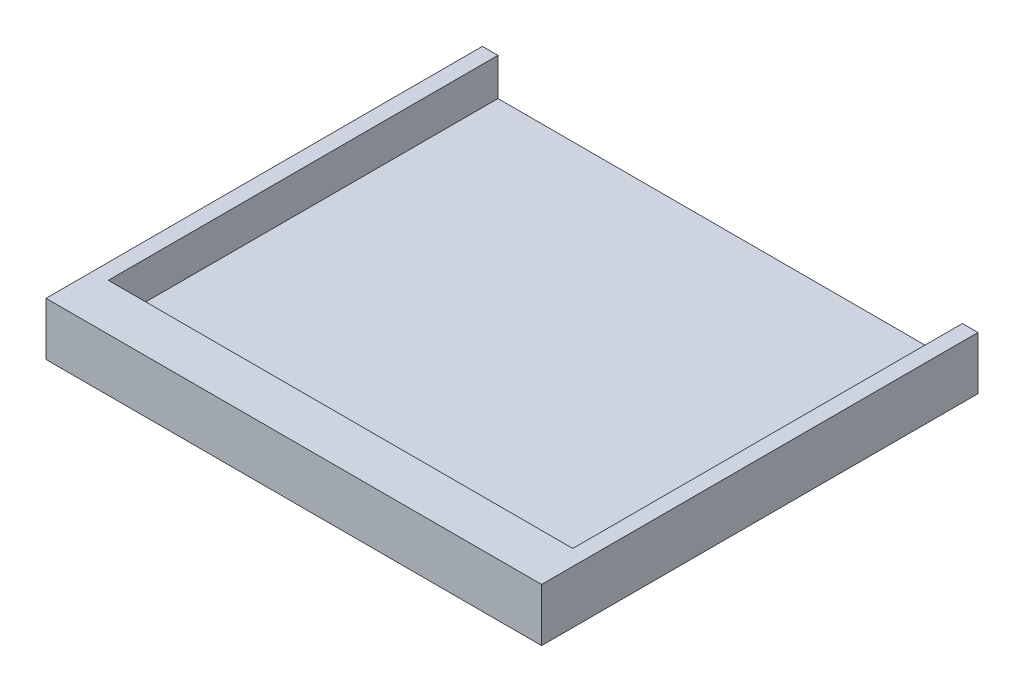
SolidWorks part; units mm, degrees
ref_plane "Front Plane" through (0, 0, 0) normal (0, 0, 1) x (1, 0, 0)
ref_plane "Top Plane" through (0, 0, 0) normal (0, 1, 0) x (1, 0, 0)
ref_plane "Right Plane" through (0, 0, 0) normal (1, 0, 0) x (0, 0, -1)
sketch "Sketch1" plane through (0, 0, 0) normal (0, 1, 0) x (1, 0, 0)
  line L1 (-14.9, -13.5) -> (14.9, -13.5)
  line L2 (-14.9, -13.5) -> (-14.9, 13.5)
  line L3 (-14.9, 13.5) -> (14.9, 13.5)
  line L4 (14.9, -13.5) -> (14.9, 13.5)
  line L5 (-14.9, -13.5) -> (14.9, 13.5) construction
  line L6 (-14.9, 13.5) -> (14.9, -13.5) construction
  point P0 (0, 0)
  dimension "D1" = 27
  dimension "D2" = 29.8
extrude "Boss-Extrude1" add sketch "Sketch1" along normal blind 1
sketch "Sketch2" plane through (0, 0, 0) normal (0, -1, 0) x (1, 0, 0)
  line L0 (15.9, 14.5) -> (-15.9, 14.5)
  line L1 (-15.9, 14.5) -> (-15.9, -13.5)
  line L3 (15.9, -13.5) -> (15.9, 14.5)
  line L4 (14.9, -13.5) -> (14.9, 13.5)
  line L5 (14.9, 13.5) -> (-14.9, 13.5)
  line L6 (-14.9, 13.5) -> (-14.9, -13.5)
  line L7 (-14.9, -13.5) -> (14.9, -13.5)
  line L8 (14.9, -13.5) -> (14.9, 13.5)
  line L9 (14.9, 13.5) -> (-14.9, 13.5)
  line L10 (-14.9, 13.5) -> (-14.9, -13.5)
  line L11 (-14.9, -13.5) -> (14.9, -13.5)
  line L12 (14.9, -13.5) -> (15.9, -13.5)
  line L13 (-14.9, -13.5) -> (-15.9, -13.5)
  line L14 (15.9, -14.5) -> (15.9, 14.5) construction
  line L15 (-15.9, -14.5) -> (15.9, -14.5) construction
  line L16 (-15.9, 14.5) -> (-15.9, -14.5) construction
  line M5 (14.9, -13.5) -> (14.9, 13.5)
  line M6 (14.9, 13.5) -> (-14.9, 13.5)
  line M7 (-14.9, 13.5) -> (-14.9, -13.5)
  dimension "D1" = 0
  dimension "D2" = 1
extrude "Boss-Extrude2" add sketch "Sketch2" against normal blind 2.4 contours L13 L12 L3 L0 L1 M7 M6 M5 | L8 L9 L10
sketch "Sketch3" plane through (0, 2.4, 0) normal (0, 1, 0) x (1, 0, 0)
  line L0 (-15.9, -14.5) -> (-15.9, 13.5) construction
  line L1 (15.9, -14.5) -> (-15.9, -14.5)
  line L2 (15.9, -14.5) -> (15.9, -11.5)
  line L3 (15.9, -11.5) -> (-15.9, -11.5)
  line L4 (-15.9, -14.5) -> (-15.9, -11.5)
  dimension "D1" = 3
extrude "Boss-Extrude3" add sketch "Sketch3" along normal blind 1
sketch "Sketch5" plane through (0, 2.4, 0) normal (0, 1, 0) x (1, 0, 0)
  line L4 (14.9, -11.5) -> (15.9, -11.5)
  line L5 (15.9, -11.5) -> (15.9, 13.5)
  line L6 (15.9, 13.5) -> (14.9, 13.5)
  line L7 (14.9, 13.5) -> (14.9, -11.5)
  line L8 (14.9, -11.5) -> (15.9, -11.5)
  line L9 (15.9, -11.5) -> (15.9, 13.5)
  line L10 (15.9, 13.5) -> (14.9, 13.5)
  line L11 (14.9, 13.5) -> (14.9, -11.5)
  dimension "D1" = 0
extrude "Boss-Extrude4" add sketch "Sketch5" along normal blind 1
sketch "Sketch6" plane through (0, 2.4, 0) normal (0, 1, 0) x (1, 0, 0)
  line L4 (-15.9, -11.5) -> (-14.9, -11.5)
  line L5 (-14.9, -11.5) -> (-14.9, 13.5)
  line L6 (-14.9, 13.5) -> (-15.9, 13.5)
  line L7 (-15.9, 13.5) -> (-15.9, -11.5)
  line L8 (-15.9, -11.5) -> (-14.9, -11.5)
  line L9 (-14.9, -11.5) -> (-14.9, 13.5)
  line L10 (-14.9, 13.5) -> (-15.9, 13.5)
  line L11 (-15.9, 13.5) -> (-15.9, -11.5)
  dimension "D1" = 0
extrude "Boss-Extrude5" add sketch "Sketch6" along normal blind 1
